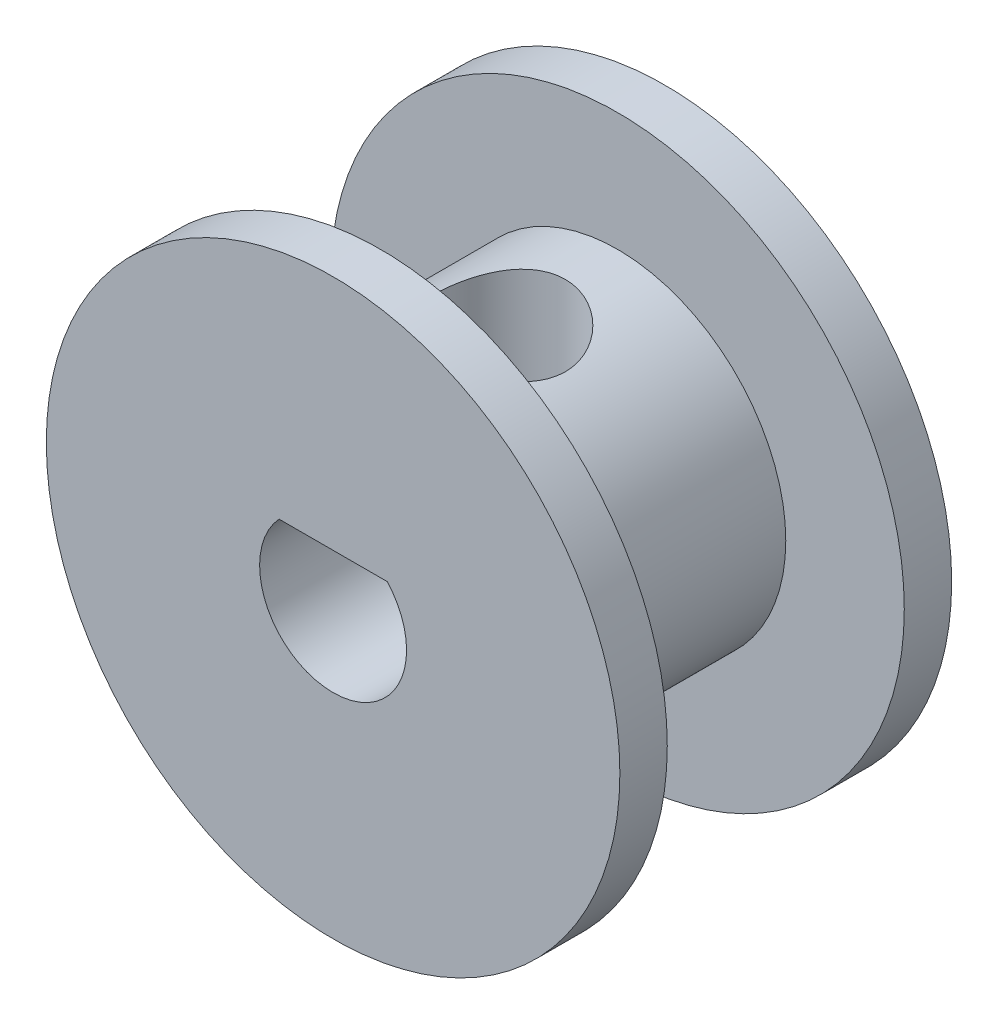
SolidWorks part; units mm, degrees
material "Thornel Mat VMA"
ref_plane "Front Plane" through (0, 0, 0) normal (0, 0, 1) x (1, 0, 0)
ref_plane "Top Plane" through (0, 0, 0) normal (0, 1, 0) x (1, 0, 0)
ref_plane "Right Plane" through (0, 0, 0) normal (1, 0, 0) x (0, 0, -1)
sketch "Sketch2" plane through (0, 0, 0) normal (1, 0, 0) x (0, 0, -1)
  line L0 (0, 1.55) -> (0, 6.05)
  line L1 (0, 6.05) -> (1, 6.05)
  line L2 (1, 6.05) -> (1, 3.55)
  line L3 (1, 3.55) -> (6, 3.55)
  line L4 (6, 3.55) -> (6, 6.05)
  line L5 (6, 6.05) -> (7, 6.05)
  line L6 (7, 6.05) -> (7, 1.55)
  line L7 (7, 1.55) -> (0, 1.55)
  line L8 (-2.1414, 0) -> (12.0517, 0) construction
  dimension "D1" = 1.55
  dimension "D2" = 7
  dimension "D3" = 1
  dimension "D4" = 1
  dimension "D5" = 2
  dimension "D6" = 4.5
revolve "Revolve1" add sketch "Sketch2" angle 360 about L8
sketch "Sketch4" plane through (0, 0, 0) normal (0, 0, 1) x (1, 0, 0)
  line L0 (-1.1402, 1.05) -> (1.1402, 1.05)
  circle A0 centre (0, 0) radius 1.55 construction
  circle A3 centre (0, 0) radius 1.55
  point P4 (0, -1.55)
  circle M4 centre (0, 0) radius 1.55
  dimension "D1" = 2.6
extrude "Boss-Extrude1" add sketch "Sketch4" against normal up to surface (7 mm away) contours L0 M4
sketch "Sketch5" plane through (0, 1.05, 0) normal (0, -1, 0) x (1, 0, 0)
  circle A0 centre (0, -3.5) radius 1.4
  dimension "D1" = 2.8
  dimension "D2" = 3.5
extrude "Cut-Extrude1" cut sketch "Sketch5" against normal through all both and the other way through all
